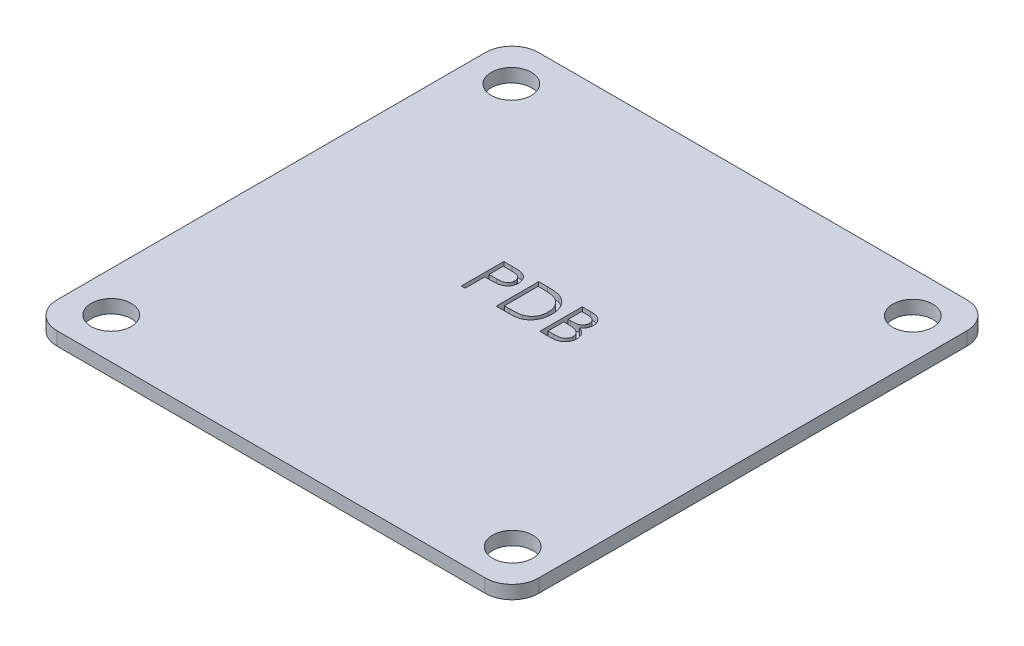
SolidWorks part; units mm, degrees
material "C-Glass Fiber"
ref_plane "Front Plane" through (0, 0, 0) normal (0, 0, 1) x (1, 0, 0)
ref_plane "Top Plane" through (0, 0, 0) normal (0, 1, 0) x (1, 0, 0)
ref_plane "Right Plane" through (0, 0, 0) normal (1, 0, 0) x (0, 0, -1)
sketch "Sketch1" plane through (0, 0, 0) normal (0, 1, 0) x (1, 0, 0)
  line L0 (3, 32.95) -> (33, 32.95) construction
  line L1 (0, 0) -> (36, 0)
  line L2 (0, 0) -> (0, 36)
  line L3 (0, 36) -> (36, 36)
  line L4 (36, 0) -> (36, 36)
  line L5 (33, 32.95) -> (33, 3.05) construction
  circle A0 centre (3, 32.95) radius 1.5
  circle A4 centre (33, 32.95) radius 1.5
  circle A5 centre (3, 3.05) radius 1.5
  circle A6 centre (33, 3.05) radius 1.5
  point P13 (18, 32.95)
  point P14 (18, 36)
  point P15 (33, 18)
  point P16 (36, 18)
  dimension "D2" = 3
  dimension "D1" = 36
  dimension "D3" = 30
  dimension "D4" = 29.9
extrude "Boss-Extrude1" add sketch "Sketch1" along normal blind 1
sketch "Sketch2" plane through (0, 0, 0) normal (0, -1, 0) x (-1, 0, 0)
  line L0 (0, 18) -> (-36, 18) construction
  line L1 (0, 36) -> (0, 0) construction
  line L2 (-36, 0) -> (-36, 36) construction
  line L3 (-36, 36) -> (0, 36) construction
  text T0 "PDB"
  dimension "D1" = 36
extrude "Cut-Extrude1" cut sketch "Sketch2" against normal blind 0.5
move or copy body "Body-Move/Copy1" bodies to move or copy 102 copy no rotation origin (0, 0.5, -18) rotation axis (1, 0, 0) rotation angle 180
fillet "Fillet1" radius 2 4 edges at (0, 0.5, -36) (0, 0.5, 0) (36, 0.5, -36) (36, 0.5, 0)
